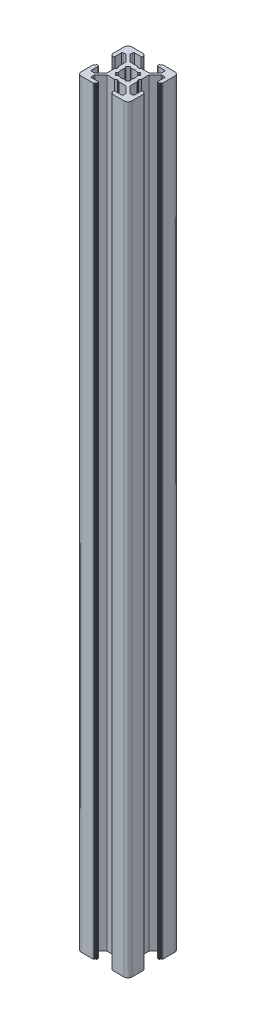
SolidWorks part; units mm, degrees
ref_plane "Front Plane" through (0, 0, 0) normal (0, 0, 1) x (1, 0, 0)
ref_plane "Top Plane" through (0, 0, 0) normal (0, 1, 0) x (1, 0, 0)
ref_plane "Right Plane" through (0, 0, 0) normal (1, 0, 0) x (0, 0, -1)
sketch "Sketch2" plane through (0, 0, 0) normal (0, 1, 0) x (1, 0, 0)
  line L0 (-10, 3.75) -> (-10, 8.5)
  line L1 (10, -10) -> (-10, -10) construction
  line L2 (10, -10) -> (10, 10) construction
  line L3 (10, 10) -> (-10, 10) construction
  line L4 (-10, -10) -> (-10, 10) construction
  line L5 (10, -10) -> (-10, 10) construction
  line L6 (10, 10) -> (-10, -10) construction
  line L7 (-9.8, 3.55) -> (-9.7, 3.55)
  line L8 (-9.5, 3.35) -> (-9.5, 3.2)
  line L9 (-9.3, 3) -> (-8.9, 3)
  line L10 (-8.5, 3.4) -> (-8.5, 5.9)
  line L11 (-8.1, 6.3) -> (-7.1728, 6.3)
  line L12 (-6.8899, 6.1828) -> (-4.6172, 3.9101)
  line L13 (-4.5, 3.6272) -> (-4.5, 0.9196)
  line L14 (-4.4732, 0.8196) -> (-4.0577, 0.1)
  line L15 (-2.4797, 1.419) -> (-2.8968, 1.8361)
  line L16 (0, 0) -> (-10, 0) construction
  line L17 (-2.4797, -1.419) -> (-2.8968, -1.8361)
  line L18 (-4.4732, -0.8196) -> (-4.0577, -0.1)
  line L19 (-4.5, -3.6272) -> (-4.5, -0.9196)
  line L20 (-6.8899, -6.1828) -> (-4.6172, -3.9101)
  line L21 (-8.1, -6.3) -> (-7.1728, -6.3)
  line L22 (-8.5, -3.4) -> (-8.5, -5.9)
  line L23 (-9.3, -3) -> (-8.9, -3)
  line L24 (-9.5, -3.35) -> (-9.5, -3.2)
  line L25 (-9.8, -3.55) -> (-9.7, -3.55)
  line L26 (-10, -3.75) -> (-10, -8.5)
  line L27 (-6.3, 8.1) -> (-6.3, 7.1728)
  line L28 (1.419, 2.4797) -> (1.8361, 2.8968)
  line L29 (6.1828, 6.8899) -> (3.9101, 4.6172)
  line L30 (6.3, 8.1) -> (6.3, 7.1728)
  line L31 (3.75, 10) -> (8.5, 10)
  line L32 (3.55, 9.8) -> (3.55, 9.7)
  line L33 (3.35, 9.5) -> (3.2, 9.5)
  line L34 (3, 9.3) -> (3, 8.9)
  line L35 (3.4, 8.5) -> (5.9, 8.5)
  line L36 (3.6272, 4.5) -> (0.9196, 4.5)
  line L37 (0.8196, 4.4732) -> (0.1, 4.0577)
  line L38 (-0.8196, 4.4732) -> (-0.1, 4.0577)
  line L39 (-1.419, 2.4797) -> (-1.8361, 2.8968)
  line L40 (-3.6272, 4.5) -> (-0.9196, 4.5)
  line L41 (-6.1828, 6.8899) -> (-3.9101, 4.6172)
  line L42 (-3.4, 8.5) -> (-5.9, 8.5)
  line L43 (-3, 9.3) -> (-3, 8.9)
  line L44 (-3.35, 9.5) -> (-3.2, 9.5)
  line L45 (-3.55, 9.8) -> (-3.55, 9.7)
  line L46 (-3.75, 10) -> (-8.5, 10)
  line L47 (10, -3.75) -> (10, -8.5)
  line L48 (9.8, -3.55) -> (9.7, -3.55)
  line L49 (9.5, -3.35) -> (9.5, -3.2)
  line L50 (9.3, -3) -> (8.9, -3)
  line L51 (8.5, -3.4) -> (8.5, -5.9)
  line L52 (6.8899, -6.1828) -> (4.6172, -3.9101)
  line L53 (4.5, -3.6272) -> (4.5, -0.9196)
  line L54 (2.4797, -1.419) -> (2.8968, -1.8361)
  line L55 (4.4732, -0.8196) -> (4.0577, -0.1)
  line L56 (4.4732, 0.8196) -> (4.0577, 0.1)
  line L57 (4.5, 3.6272) -> (4.5, 0.9196)
  line L58 (8.5, 3.4) -> (8.5, 5.9)
  line L59 (9.3, 3) -> (8.9, 3)
  line L60 (9.5, 3.35) -> (9.5, 3.2)
  line L61 (9.8, 3.55) -> (9.7, 3.55)
  line L62 (10, 3.75) -> (10, 8.5)
  line L63 (8.1, 6.3) -> (7.1728, 6.3)
  line L64 (6.8899, 6.1828) -> (4.6172, 3.9101)
  line L65 (2.4797, 1.419) -> (2.8968, 1.8361)
  line L66 (8.1, -6.3) -> (7.1728, -6.3)
  line L67 (-3.75, -10) -> (-8.5, -10)
  line L68 (-3.55, -9.8) -> (-3.55, -9.7)
  line L69 (-3.35, -9.5) -> (-3.2, -9.5)
  line L70 (-3, -9.3) -> (-3, -8.9)
  line L71 (-3.4, -8.5) -> (-5.9, -8.5)
  line L72 (-6.3, -8.1) -> (-6.3, -7.1728)
  line L73 (-6.1828, -6.8899) -> (-3.9101, -4.6172)
  line L74 (-3.6272, -4.5) -> (-0.9196, -4.5)
  line L75 (-0.8196, -4.4732) -> (-0.1, -4.0577)
  line L76 (-1.419, -2.4797) -> (-1.8361, -2.8968)
  line L77 (1.419, -2.4797) -> (1.8361, -2.8968)
  line L78 (0.8196, -4.4732) -> (0.1, -4.0577)
  line L79 (3.6272, -4.5) -> (0.9196, -4.5)
  line L80 (6.1828, -6.8899) -> (3.9101, -4.6172)
  line L81 (6.3, -8.1) -> (6.3, -7.1728)
  line L82 (3.4, -8.5) -> (5.9, -8.5)
  line L83 (3, -9.3) -> (3, -8.9)
  line L84 (3.35, -9.5) -> (3.2, -9.5)
  line L85 (3.55, -9.8) -> (3.55, -9.7)
  line L86 (3.75, -10) -> (8.5, -10)
  arc A0 (-10, 8.5) -> (-8.5, 10) centre (-8.5, 8.5) cw
  arc A1 (-2.452, -1.2451) -> (-2.452, 1.2451) centre (0, 0) cw
  arc A2 (-2.9138, 2.0279) -> (-2.0279, 2.9138) centre (0, 0) cw
  arc A3 (-2.9138, -2.0279) -> (-2.0279, -2.9138) centre (0, 0) ccw
  arc A4 (-10, -8.5) -> (-8.5, -10) centre (-8.5, -8.5) ccw
  arc A5 (2.0279, 2.9138) -> (2.9138, 2.0279) centre (0, 0) cw
  arc A6 (8.5, 10) -> (10, 8.5) centre (8.5, 8.5) cw
  arc A7 (1.2451, 2.452) -> (-1.2451, 2.452) centre (0, 0) ccw
  arc A8 (2.452, 1.2451) -> (2.452, -1.2451) centre (0, 0) cw
  arc A9 (2.0279, -2.9138) -> (2.9138, -2.0279) centre (0, 0) ccw
  arc A10 (-1.2451, -2.452) -> (1.2451, -2.452) centre (0, 0) ccw
  arc A11 (8.5, -10) -> (10, -8.5) centre (8.5, -8.5) ccw
  arc A12 (-3.55, 9.8) -> (-3.75, 10) centre (-3.75, 9.8) ccw
  arc A13 (-3.35, 9.5) -> (-3.55, 9.7) centre (-3.35, 9.7) cw
  arc A14 (-3, 9.3) -> (-3.2, 9.5) centre (-3.2, 9.3) ccw
  arc A15 (3.75, 10) -> (3.55, 9.8) centre (3.75, 9.8) ccw
  arc A16 (3.2, 9.5) -> (3, 9.3) centre (3.2, 9.3) ccw
  arc A17 (3.55, 9.7) -> (3.35, 9.5) centre (3.35, 9.7) cw
  arc A18 (9.8, 3.55) -> (10, 3.75) centre (9.8, 3.75) ccw
  arc A19 (9.5, 3.35) -> (9.7, 3.55) centre (9.7, 3.35) cw
  arc A20 (9.3, 3) -> (9.5, 3.2) centre (9.3, 3.2) ccw
  arc A21 (9.5, -3.2) -> (9.3, -3) centre (9.3, -3.2) ccw
  arc A22 (9.7, -3.55) -> (9.5, -3.35) centre (9.7, -3.35) cw
  arc A23 (10, -3.75) -> (9.8, -3.55) centre (9.8, -3.75) ccw
  arc A24 (3.55, -9.8) -> (3.75, -10) centre (3.75, -9.8) ccw
  arc A25 (3.35, -9.5) -> (3.55, -9.7) centre (3.35, -9.7) cw
  arc A26 (3, -9.3) -> (3.2, -9.5) centre (3.2, -9.3) ccw
  arc A27 (-3.75, -10) -> (-3.55, -9.8) centre (-3.75, -9.8) ccw
  arc A28 (-3.55, -9.7) -> (-3.35, -9.5) centre (-3.35, -9.7) cw
  arc A29 (-3.2, -9.5) -> (-3, -9.3) centre (-3.2, -9.3) ccw
  arc A30 (4.4732, 0.8196) -> (4.5, 0.9196) centre (4.3, 0.9196) ccw
  arc A31 (4.0577, -0.1) -> (4.0577, 0.1) centre (4.2309, 0) cw
  arc A32 (4.5, -0.9196) -> (4.4732, -0.8196) centre (4.3, -0.9196) ccw
  arc A33 (0.8196, -4.4732) -> (0.9196, -4.5) centre (0.9196, -4.3) ccw
  arc A34 (-0.1, -4.0577) -> (0.1, -4.0577) centre (0, -4.2309) cw
  arc A35 (-0.9196, -4.5) -> (-0.8196, -4.4732) centre (-0.9196, -4.3) ccw
  arc A36 (-4.4732, -0.8196) -> (-4.5, -0.9196) centre (-4.3, -0.9196) ccw
  arc A37 (-4.0577, 0.1) -> (-4.0577, -0.1) centre (-4.2309, 0) cw
  arc A38 (-4.5, 0.9196) -> (-4.4732, 0.8196) centre (-4.3, 0.9196) ccw
  arc A39 (0.9196, 4.5) -> (0.8196, 4.4732) centre (0.9196, 4.3) ccw
  arc A40 (0.1, 4.0577) -> (-0.1, 4.0577) centre (0, 4.2309) cw
  arc A41 (-0.8196, 4.4732) -> (-0.9196, 4.5) centre (-0.9196, 4.3) ccw
  arc A42 (-9.8, -3.55) -> (-10, -3.75) centre (-9.8, -3.75) ccw
  arc A43 (-9.5, -3.35) -> (-9.7, -3.55) centre (-9.7, -3.35) cw
  arc A44 (-9.3, -3) -> (-9.5, -3.2) centre (-9.3, -3.2) ccw
  arc A45 (-9.5, 3.2) -> (-9.3, 3) centre (-9.3, 3.2) ccw
  arc A46 (-9.7, 3.55) -> (-9.5, 3.35) centre (-9.7, 3.35) cw
  arc A47 (-10, 3.75) -> (-9.8, 3.55) centre (-9.8, 3.75) ccw
  arc A48 (-8.9, 3) -> (-8.5, 3.4) centre (-8.9, 3.4) ccw
  arc A49 (-8.5, 5.9) -> (-8.1, 6.3) centre (-8.1, 5.9) cw
  arc A50 (-3.4, 8.5) -> (-3, 8.9) centre (-3.4, 8.9) ccw
  arc A51 (-6.3, 8.1) -> (-5.9, 8.5) centre (-5.9, 8.1) cw
  arc A52 (-6.3, 7.1728) -> (-6.1828, 6.8899) centre (-5.9, 7.1728) ccw
  arc A53 (-7.1728, 6.3) -> (-6.8899, 6.1828) centre (-7.1728, 5.9) cw
  arc A54 (-4.6172, 3.9101) -> (-4.5, 3.6272) centre (-4.9, 3.6272) cw
  arc A55 (-3.6272, 4.5) -> (-3.9101, 4.6172) centre (-3.6272, 4.9) cw
  arc A56 (8.5, 3.4) -> (8.9, 3) centre (8.9, 3.4) ccw
  arc A57 (8.5, 5.9) -> (8.1, 6.3) centre (8.1, 5.9) ccw
  arc A58 (7.1728, 6.3) -> (6.8899, 6.1828) centre (7.1728, 5.9) ccw
  arc A59 (3, 8.9) -> (3.4, 8.5) centre (3.4, 8.9) ccw
  arc A60 (6.3, 8.1) -> (5.9, 8.5) centre (5.9, 8.1) ccw
  arc A61 (6.1828, 6.8899) -> (6.3, 7.1728) centre (5.9, 7.1728) ccw
  arc A62 (3.9101, 4.6172) -> (3.6272, 4.5) centre (3.6272, 4.9) cw
  arc A63 (4.5, 3.6272) -> (4.6172, 3.9101) centre (4.9, 3.6272) cw
  arc A64 (8.9, -3) -> (8.5, -3.4) centre (8.9, -3.4) ccw
  arc A65 (8.5, -5.9) -> (8.1, -6.3) centre (8.1, -5.9) cw
  arc A66 (6.8899, -6.1828) -> (7.1728, -6.3) centre (7.1728, -5.9) ccw
  arc A67 (4.6172, -3.9101) -> (4.5, -3.6272) centre (4.9, -3.6272) cw
  arc A68 (3.6272, -4.5) -> (3.9101, -4.6172) centre (3.6272, -4.9) cw
  arc A69 (6.1828, -6.8899) -> (6.3, -7.1728) centre (5.9, -7.1728) cw
  arc A70 (6.3, -8.1) -> (5.9, -8.5) centre (5.9, -8.1) cw
  arc A71 (3.4, -8.5) -> (3, -8.9) centre (3.4, -8.9) ccw
  arc A72 (-3, -8.9) -> (-3.4, -8.5) centre (-3.4, -8.9) ccw
  arc A73 (-5.9, -8.5) -> (-6.3, -8.1) centre (-5.9, -8.1) cw
  arc A74 (-6.3, -7.1728) -> (-6.1828, -6.8899) centre (-5.9, -7.1728) cw
  arc A75 (-3.9101, -4.6172) -> (-3.6272, -4.5) centre (-3.6272, -4.9) cw
  arc A76 (-4.5, -3.6272) -> (-4.6172, -3.9101) centre (-4.9, -3.6272) cw
  arc A77 (-6.8899, -6.1828) -> (-7.1728, -6.3) centre (-7.1728, -5.9) cw
  arc A78 (-8.1, -6.3) -> (-8.5, -5.9) centre (-8.1, -5.9) cw
  arc A79 (-8.5, -3.4) -> (-8.9, -3) centre (-8.9, -3.4) ccw
  arc A80 (-2.4797, -1.419) -> (-2.452, -1.2451) centre (-2.5858, -1.313) ccw
  arc A81 (-2.9138, -2.0279) -> (-2.8968, -1.8361) centre (-2.7907, -1.9422) cw
  arc A82 (-1.8361, -2.8968) -> (-2.0279, -2.9138) centre (-1.9422, -2.7907) cw
  arc A83 (-1.2451, -2.452) -> (-1.419, -2.4797) centre (-1.313, -2.5858) ccw
  arc A84 (1.2451, -2.452) -> (1.419, -2.4797) centre (1.313, -2.5858) cw
  arc A85 (2.0279, -2.9138) -> (1.8361, -2.8968) centre (1.9422, -2.7907) cw
  arc A86 (2.9138, -2.0279) -> (2.8968, -1.8361) centre (2.7907, -1.9422) ccw
  arc A87 (2.452, -1.2451) -> (2.4797, -1.419) centre (2.5858, -1.313) ccw
  arc A88 (2.452, 1.2451) -> (2.4797, 1.419) centre (2.5858, 1.313) cw
  arc A89 (2.8968, 1.8361) -> (2.9138, 2.0279) centre (2.7907, 1.9422) ccw
  arc A90 (2.0279, 2.9138) -> (1.8361, 2.8968) centre (1.9422, 2.7907) ccw
  arc A91 (1.419, 2.4797) -> (1.2451, 2.452) centre (1.313, 2.5858) cw
  arc A92 (-1.2451, 2.452) -> (-1.419, 2.4797) centre (-1.313, 2.5858) cw
  arc A93 (-1.8361, 2.8968) -> (-2.0279, 2.9138) centre (-1.9422, 2.7907) ccw
  arc A94 (-2.8968, 1.8361) -> (-2.9138, 2.0279) centre (-2.7907, 1.9422) cw
  arc A95 (-2.452, 1.2451) -> (-2.4797, 1.419) centre (-2.5858, 1.313) ccw
  point P0 (0, 0)
  point P119 (-3.55, 10)
  point P122 (-3.55, 9.5)
  point P125 (-3, 9.5)
  point P128 (3.55, 10)
  point P131 (3, 9.5)
  point P134 (3.55, 9.5)
  point P137 (10, 3.55)
  point P140 (9.5, 3.55)
  point P143 (9.5, 3)
  point P146 (9.5, -3)
  point P149 (9.5, -3.55)
  point P152 (10, -3.55)
  point P155 (3.55, -10)
  point P158 (3.55, -9.5)
  point P161 (3, -9.5)
  point P164 (-3.55, -10)
  point P167 (-3.55, -9.5)
  point P170 (-3, -9.5)
  point P173 (4.5, 0.866)
  point P176 (4, 0)
  point P179 (4.5, -0.866)
  point P182 (0.866, -4.5)
  point P185 (0, -4)
  point P188 (-0.866, -4.5)
  point P191 (-4.5, -0.866)
  point P194 (-4, 0)
  point P197 (-4.5, 0.866)
  point P200 (0.866, 4.5)
  point P203 (0, 4)
  point P206 (-0.866, 4.5)
  point P209 (-10, -3.55)
  point P212 (-9.5, -3.55)
  point P215 (-9.5, -3)
  point P218 (-9.5, 3)
  point P221 (-9.5, 3.55)
  point P224 (-10, 3.55)
  point P227 (-8.5, 3)
  point P230 (-8.5, 6.3)
  point P233 (-3, 8.5)
  point P236 (-6.3, 8.5)
  point P239 (-6.3, 7.0071)
  point P242 (-7.0071, 6.3)
  point P245 (-4.5, 3.7929)
  point P248 (-3.7929, 4.5)
  point P251 (8.5, 3)
  point P254 (8.5, 6.3)
  point P257 (7.0071, 6.3)
  point P260 (3, 8.5)
  point P263 (6.3, 8.5)
  point P266 (6.3, 7.0071)
  point P269 (3.7929, 4.5)
  point P272 (4.5, 3.7929)
  point P275 (8.5, -3)
  point P278 (8.5, -6.3)
  point P281 (7.0071, -6.3)
  point P284 (4.5, -3.7929)
  point P287 (3.7929, -4.5)
  point P290 (6.3, -7.0071)
  point P293 (6.3, -8.5)
  point P296 (3, -8.5)
  point P299 (-3, -8.5)
  point P302 (-6.3, -8.5)
  point P305 (-6.3, -7.0071)
  point P308 (-3.7929, -4.5)
  point P311 (-4.5, -3.7929)
  point P314 (-7.0071, -6.3)
  point P317 (-8.5, -6.3)
  point P320 (-8.5, -3)
  point P323 (-2.4012, -1.3405)
  point P326 (-2.9839, -1.9232)
  point P329 (-1.9232, -2.9839)
  point P332 (-1.3405, -2.4012)
  point P335 (1.3405, -2.4012)
  point P338 (1.9232, -2.9839)
  point P341 (2.9839, -1.9232)
  point P344 (2.4012, -1.3405)
  point P347 (2.4012, 1.3405)
  point P350 (2.9839, 1.9232)
  point P353 (1.9232, 2.9839)
  point P356 (1.3405, 2.4012)
  point P359 (-1.3405, 2.4012)
  point P362 (-1.9232, 2.9839)
  point P365 (-2.9839, 1.9232)
  point P368 (-2.4012, 1.3405)
  dimension "D3" = 1.5
  dimension "D10" = 2.75
  dimension "D11" = 3.55
  dimension "D16" = 0.2
  dimension "D17" = 0.4
  dimension "D18" = 0.15
  dimension "D1" = 20
  dimension "D2" = 20
  dimension "D4" = 6.45
  dimension "D5" = 0.5
  dimension "D6" = 1
  dimension "D7" = 7
  dimension "D8" = 4
  dimension "D9" = 1
  dimension "D12" = 1.5
  dimension "D13" = 3.3
  dimension "D14" = 4
  dimension "D15" = 60
extrude "Boss-Extrude1" add sketch "Sketch2" along normal mid plane 300 contours A95 A1 A80 L17 A81 A3 A82 L76 A83 A10 A84 L77 A85 A9 A86 L54 A87 A8 A88 L65 A89 A5 A90 L28 A91 A7 A92 L39 A93 A2 A94 L15 | L10 A49 L11 A53 L12 A54 L13 A38 L14 A37 L18 A36 L19 A76 L20 A77 L21 A78 L22 A79 L23 A44 L24 A43 L25 A42 L26 A4 L67 A27 L68 A28 L69 A29 L70 A72 L71 A73 L72 A74 L73 A75 L74 A35 L75 A34 L78 A33 L79 A68 L80 A69 L81 A70 L82 A71 L83 A26 L84 A25 L85 A24 L86 A11 L47 A23 L48 A22 L49 A21 L50 A64 L51 A65 L66 A66 L52 A67 L53 A32 L55 A31 L56 A30 L57 A63 L64 A58 L63 A57 L58 A56 L59 A20 L60 A19 L61 A18 L62 A6 L31 A15 L32 A17 L33 A16 L34 A59 L35 A60 L30 A61 L29 A62 L36 A39 L37 A40 L38 A41 L40 A55 L41 A52 L27 A51 L42 A50 L43 A14 L44 A13 L45 A12 L46 A0 L0 A47 L7 A46 L8 A45 L9 A48
